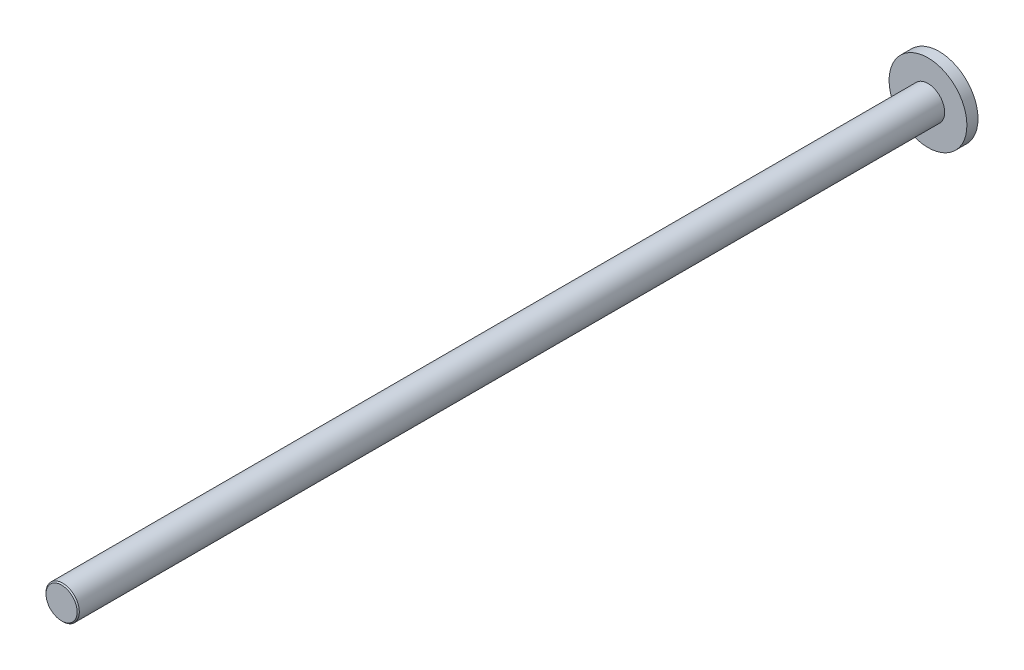
SolidWorks part; units mm, degrees
material "Brass"
ref_plane "Front Plane" through (0, 0, 0) normal (0, 0, 1) x (1, 0, 0)
ref_plane "Top Plane" through (0, 0, 0) normal (0, 1, 0) x (1, 0, 0)
ref_plane "Right Plane" through (0, 0, 0) normal (1, 0, 0) x (0, 0, -1)
other "Configuration Table"
sketch "Sketch2" plane through (0, 0, 0) normal (0, 0, 1) x (1, 0, 0)
  circle A0 centre (0, 0) radius 3.5
  dimension "D1" = 7
extrude "Boss-Extrude1" add sketch "Sketch2" along normal blind 1
sketch "Sketch3" plane through (0, 0, 1) normal (0, 0, 1) x (1, 0, 0)
  circle A0 centre (0, 0) radius 1.5
  dimension "D1" = 3
extrude "Boss-Extrude2" add sketch "Sketch3" along normal blind 78
chamfer "Chamfer1" distance 0.1 angle 45 1 edges at (1.5, 0, 79)
